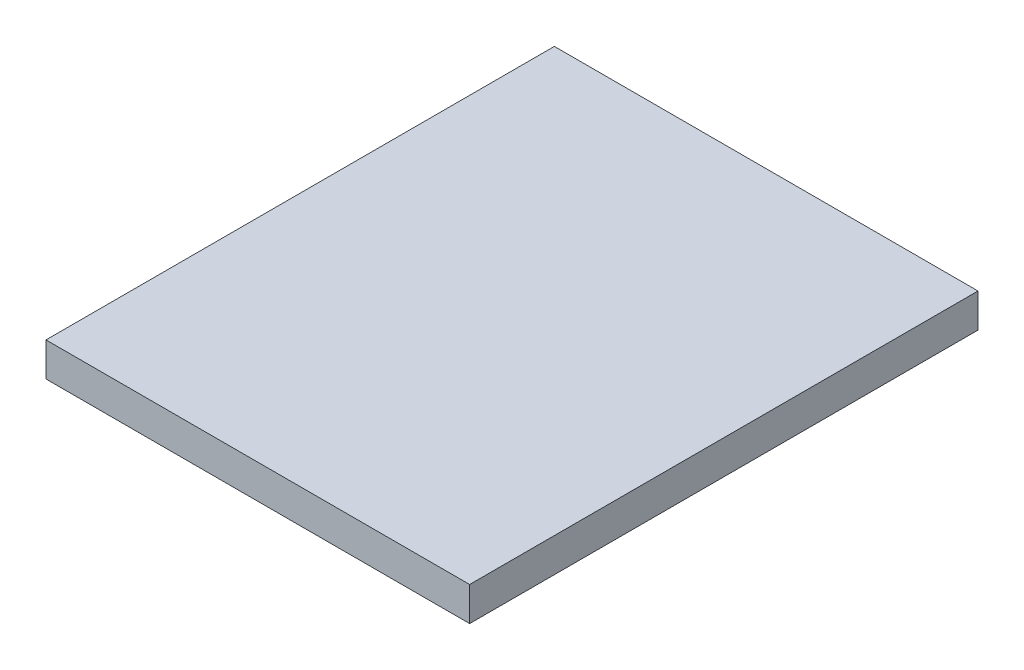
SolidWorks part; units mm, degrees
ref_plane "Front Plane" through (0, 0, 0) normal (0, 0, 1) x (1, 0, 0)
ref_plane "Top Plane" through (0, 0, 0) normal (0, 1, 0) x (1, 0, 0)
ref_plane "Right Plane" through (0, 0, 0) normal (1, 0, 0) x (0, 0, -1)
sketch "Sketch1" plane through (0, 0, 0) normal (0, 1, 0) x (1, 0, 0)
  line L1 (-50, 60) -> (50, 60)
  line L2 (-50, 60) -> (-50, -60)
  line L3 (-50, -60) -> (50, -60)
  line L4 (50, 60) -> (50, -60)
  line L5 (-50, 60) -> (50, -60) construction
  line L6 (-50, -60) -> (50, 60) construction
  point P0 (0, 0)
  dimension "D1" = 100
  dimension "D2" = 120
extrude "Boss-Extrude1" add sketch "Sketch1" along normal blind 8
